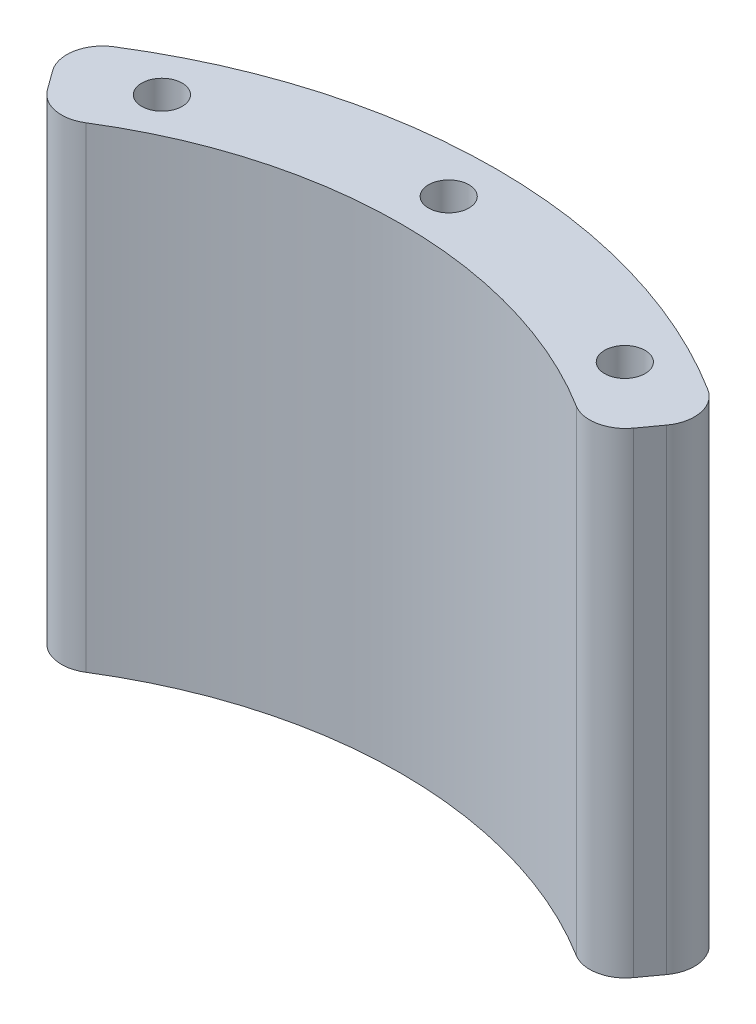
SolidWorks part; units mm, degrees
ref_plane "前视基准面" through (0, 0, 0) normal (0, 0, 1) x (1, 0, 0)
ref_plane "上视基准面" through (0, 0, 0) normal (0, 1, 0) x (1, 0, 0)
ref_plane "右视基准面" through (0, 0, 0) normal (1, 0, 0) x (0, 0, -1)
other "Configuration Table"
sketch "草图1" plane through (0, 0, 0) normal (0, 1, 0) x (1, 0, 0)
  line L0 (-22.9236, 31.5517) -> (-27.6259, 38.0238)
  line L1 (0, 0) -> (0, 47) construction
  line L2 (22.9236, 31.5517) -> (27.6259, 38.0238)
  line L3 (-22.9236, 31.5517) -> (0, 0) construction
  line L4 (22.9236, 31.5517) -> (0, 0) construction
  line L5 (-19.4516, 38.3488) -> (0, 0) construction
  line L6 (0, 0) -> (19.4516, 38.3488) construction
  arc A0 (22.9236, 31.5517) -> (-22.9236, 31.5517) centre (0, 0) ccw
  arc A1 (27.6259, 38.0238) -> (-27.6259, 38.0238) centre (0, 0) ccw
  arc A2 (-25.2748, 34.7877) -> (25.2748, 34.7877) centre (0, 0) cw construction
  circle A3 centre (0, 43) radius 1.7
  circle A4 centre (19.4516, 38.3488) radius 1.7
  circle A5 centre (-19.4516, 38.3488) radius 1.7
  dimension "D1" = 43
  dimension "D2" = 8
  dimension "D6" = 3.4
  dimension "D3" = 20
  dimension "D4" = 36
extrude "凸台-拉伸1" add sketch "草图1" along normal blind 40
fillet "圆角1" radius 3 4 edges at (-22.9236, 20, -31.5517) (-27.6259, 20, -38.0238) (22.9236, 20, -31.5517) (27.6259, 20, -38.0238)
